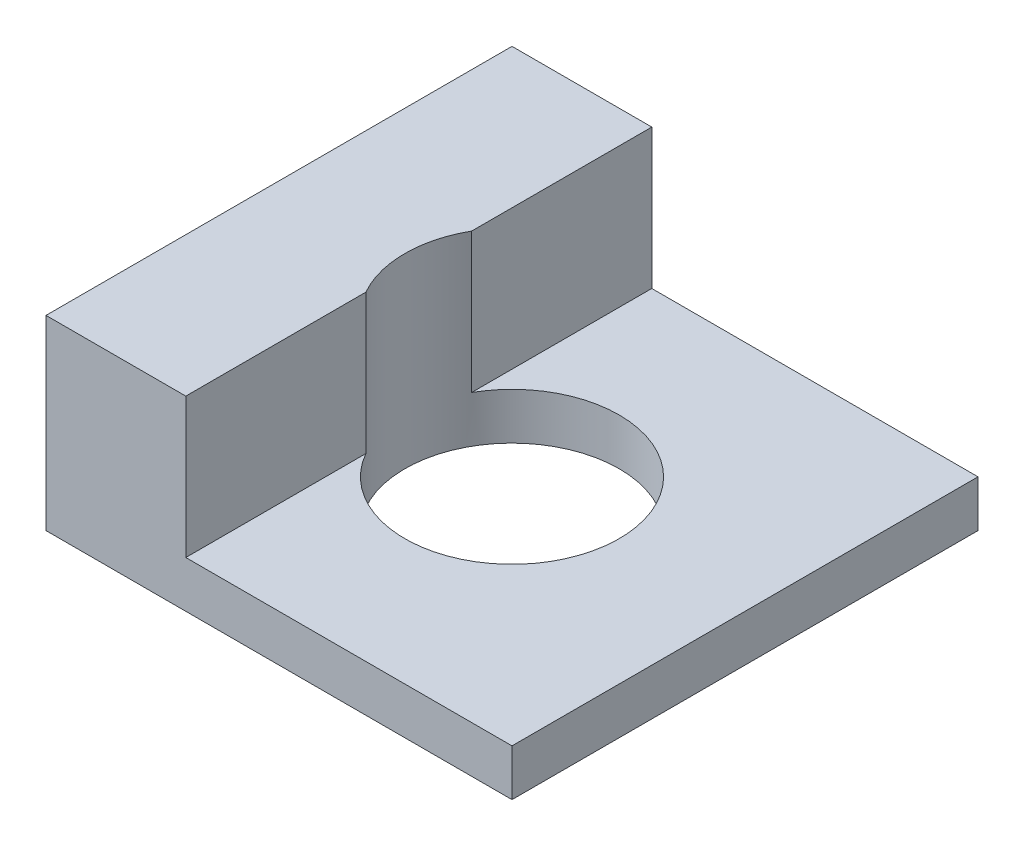
SolidWorks part; units mm, degrees
ref_plane "Front Plane" through (0, 0, 0) normal (0, 0, 1) x (1, 0, 0)
ref_plane "Top Plane" through (0, 0, 0) normal (0, 1, 0) x (1, 0, 0)
ref_plane "Right Plane" through (0, 0, 0) normal (1, 0, 0) x (0, 0, -1)
sketch "Sketch1" plane through (0, 0, 0) normal (0, 1, 0) x (1, 0, 0)
  line L1 (0, 0) -> (50, 0)
  line L2 (0, 0) -> (0, 50)
  line L3 (0, 50) -> (50, 50)
  line L4 (50, 0) -> (50, 50)
  dimension "D1" = 50
  dimension "D2" = 50
extrude "Boss-Extrude1" add sketch "Sketch1" along normal blind 20
sketch "Sketch2" plane through (0, 0, 0) normal (0, -1, 0) x (1, 0, 0)
  line L0 (25, 0) -> (25, -50) construction
  line L1 (0, 0) -> (50, 0) construction
  line L2 (50, -50) -> (0, -50) construction
  line L3 (50, -25) -> (0, -25) construction
  line L4 (50, 0) -> (50, -50) construction
  line L5 (0, -50) -> (0, 0) construction
  circle A0 centre (25, -25) radius 11.5
  point P14 (9.5, -9.5)
  point P15 (40.5, -9.5)
  point P16 (40.5, -40.5)
  point P17 (9.5, -40.5)
  dimension "D1" = 23
  dimension "D2" = 15.5
  dimension "D3" = 15.5
extrude "Cut-Extrude1" cut sketch "Sketch2" against normal through all
sketch "Sketch3" plane through (0, 20, 0) normal (0, 1, 0) x (1, 0, 0)
  line L1 (15, 56.0462) -> (53.4731, 56.0462)
  line L2 (15, 56.0462) -> (15, -2.8794)
  line L3 (15, -2.8794) -> (53.4731, -2.8794)
  line L4 (53.4731, 56.0462) -> (53.4731, -2.8794)
  line L5 (0, 50) -> (0, 0) construction
  dimension "D1" = 15
extrude "Cut-Extrude2" cut sketch "Sketch3" against normal blind 15
